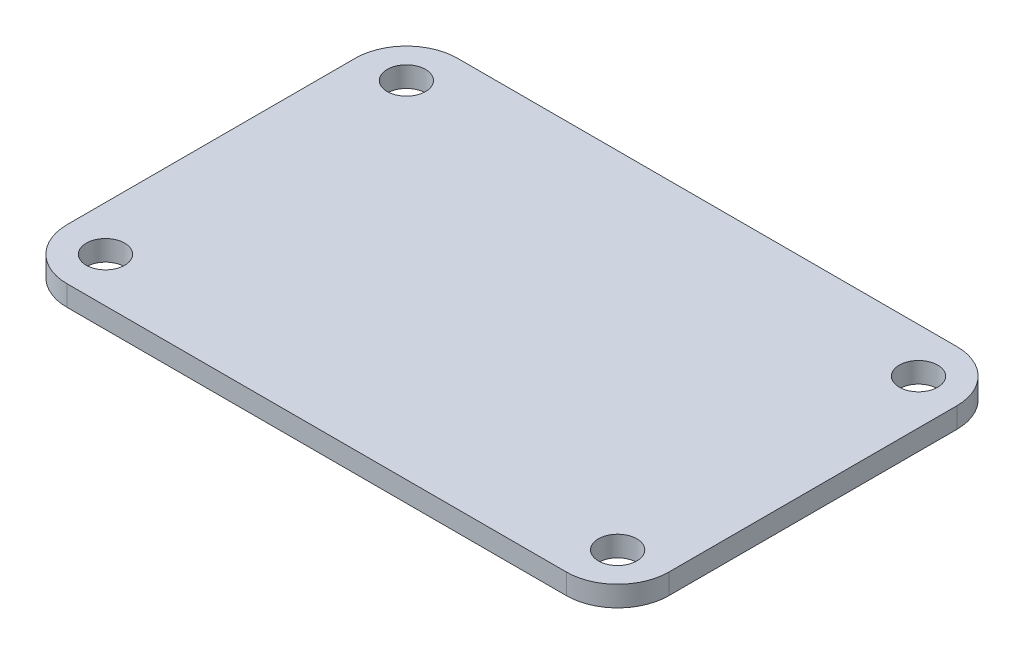
SolidWorks part; units mm, degrees
material "电源线路板"
ref_plane "前视基准面" through (0, 0, 0) normal (0, 0, 1) x (1, 0, 0)
ref_plane "上视基准面" through (0, 0, 0) normal (0, 1, 0) x (1, 0, 0)
ref_plane "右视基准面" through (0, 0, 0) normal (1, 0, 0) x (0, 0, -1)
other "Configuration Table"
sketch "草图1" plane through (0, 0, 0) normal (0, 1, 0) x (1, 0, 0)
  line L1 (-16.0006, 16.1749) -> (22.9994, 16.1749)
  line L2 (-20.0006, 12.1749) -> (-20.0006, -10.3251)
  line L3 (-16.0006, -14.3251) -> (22.9994, -14.3251)
  line L4 (26.9994, 12.1749) -> (26.9994, -10.3251)
  arc A0 (-20.0006, 12.1749) -> (-16.0006, 16.1749) centre (-16.0006, 12.1749) cw
  arc A1 (26.9994, 12.1749) -> (22.9994, 16.1749) centre (22.9994, 12.1749) ccw
  arc A2 (22.9994, -14.3251) -> (26.9994, -10.3251) centre (22.9994, -10.3251) ccw
  arc A3 (-20.0006, -10.3251) -> (-16.0006, -14.3251) centre (-16.0006, -10.3251) ccw
  circle A4 centre (-16.5006, 12.6749) radius 1.5
  circle A5 centre (23.4994, 12.6749) radius 1.5
  circle A6 centre (-16.5006, -10.8251) radius 1.5
  circle A7 centre (23.4994, -10.8251) radius 1.5
  point P6 (-20.0006, 16.1749)
  point P9 (26.9994, 16.1749)
  point P14 (-20.0006, -14.3251)
  dimension "D3" = 4
  dimension "D4" = 4
  dimension "D5" = 4
  dimension "D6" = 4
  dimension "D7" = 40
  dimension "D1" = 47
  dimension "D2" = 30.5
  dimension "D8" = 40
  dimension "D9" = 0
  dimension "D10" = 0
  dimension "D11" = 0
  dimension "D12" = 23.5
  dimension "D13" = 3.5
  dimension "D14" = 3.5
extrude "凸台-拉伸1" add sketch "草图1" along normal blind 1.6
